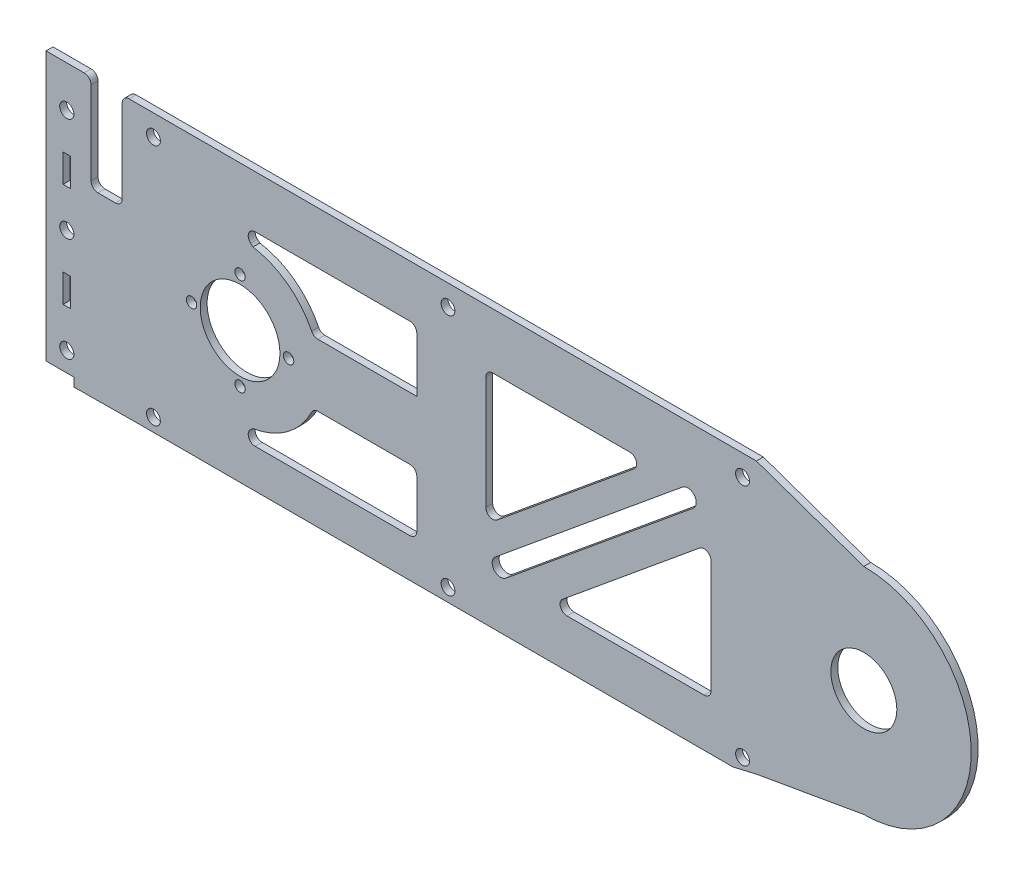
SolidWorks part; units mm, degrees
ref_plane "前视基准面" through (0, 0, 0) normal (0, 0, 1) x (1, 0, 0)
ref_plane "上视基准面" through (0, 0, 0) normal (0, 1, 0) x (1, 0, 0)
ref_plane "右视基准面" through (0, 0, 0) normal (1, 0, 0) x (0, 0, -1)
sketch "草图1" plane through (0, 0, 0) normal (0, 0, 1) x (1, 0, 0)
  line L0 (1.6429, 32.0043) -> (1.6429, 27.9043)
  line L1 (1.6429, 18.9543) -> (1.6429, 10.9543) construction
  line L2 (0.5929, 10.9043) -> (2.6929, 10.9043)
  line L3 (0.5929, 10.9043) -> (0.5929, 19.0043)
  line L4 (0.5929, 19.0043) -> (2.6929, 19.0043)
  line L5 (2.6929, 10.9043) -> (2.6929, 19.0043)
  line L6 (0.5929, 10.9043) -> (2.6929, 19.0043) construction
  line L7 (0.5929, 19.0043) -> (2.6929, 10.9043) construction
  line L12 (1.6429, -0.0457) -> (-4.3571, -0.0457) construction
  line L13 (-4.3571, -0.0457) -> (-4.3571, 41.8043)
  line L14 (-4.3571, 41.8043) -> (262.6429, 41.8043) construction
  line L15 (262.6429, 41.8043) -> (262.6429, -38.1957) construction
  line L18 (51.6429, -0.0457) -> (97.8433, -0.0457) construction
  line L19 (51.6429, -0.0457) -> (231.6429, -0.0457) construction
  line L21 (200.6429, -0.0457) -> (200.6429, 41.8043) construction
  line L23 (200.6429, 41.8043) -> (231.6429, 30.9543)
  line L26 (231.6429, -31.0457) -> (200.6561, -36.4559)
  line L28 (-4.3571, 41.8043) -> (8.6429, 41.8043)
  line L29 (1.6429, -0.0457) -> (37.6429, -0.0457) construction
  line L32 (22.4658, -38.0457) -> (193.8469, -38.0457)
  line L42 (17.6429, 13.8043) -> (17.6429, 41.8043)
  line L43 (17.6429, 41.8043) -> (200.6429, 41.8043)
  line L44 (8.6429, 41.8043) -> (8.6429, 13.8043)
  line L45 (8.6429, 13.8043) -> (17.6429, 13.8043)
  line L47 (193.8469, -38.0457) -> (200.6561, -36.4559)
  line L48 (0.5929, -19.0957) -> (2.6929, -10.9957) construction
  line L49 (0.5929, -10.9957) -> (2.6929, -19.0957) construction
  line L50 (1.6429, -19.0457) -> (1.6429, -11.0457) construction
  line L51 (2.6929, -10.9957) -> (2.6929, -19.0957)
  line L52 (0.5929, -19.0957) -> (2.6929, -19.0957)
  line L53 (0.5929, -10.9957) -> (0.5929, -19.0957)
  line L54 (0.5929, -10.9957) -> (2.6929, -10.9957)
  line L55 (-4.3571, -35.7026) -> (3.7929, -35.7026)
  line L56 (3.7929, -35.7026) -> (3.7929, -38.1957)
  line L57 (3.7929, -38.1957) -> (22.4658, -38.0457)
  line L58 (-4.3571, -35.7026) -> (-4.3571, -0.0457)
  circle A0 centre (1.6429, 29.9543) radius 2.05
  circle A1 centre (1.6429, -0.0457) radius 2.05
  circle A2 centre (1.6429, -30.0457) radius 2.05
  circle A3 centre (51.6429, -0.0457) radius 11.5
  circle A4 centre (51.6429, -0.0457) radius 14 construction
  circle A5 centre (51.6429, -14.0457) radius 1.5
  circle A12 centre (37.6429, -0.0457) radius 1.5
  circle A13 centre (51.6429, 13.9543) radius 1.5
  circle A14 centre (65.6429, -0.0457) radius 1.5
  circle A15 centre (231.6429, -0.0457) radius 9.525
  circle A16 centre (231.6429, -0.0457) radius 31 construction
  arc A17 (231.6429, 30.9543) -> (231.6429, -31.0457) centre (231.6429, -0.0457) cw
  point P6 (1.6429, 14.9543)
  point P56 (1.6429, -15.0457)
  dimension "D3" = 23
  dimension "D4" = 4
  dimension "D13" = 19.05
  dimension "D1" = 8.1
  dimension "D2" = 2.1
  dimension "D5" = 50
  dimension "D6" = 28
  dimension "D7" = 15
  dimension "D8" = 60
  dimension "D9" = 30
  dimension "D11" = 41.85
  dimension "D12" = 31
  dimension "D14" = 180
  dimension "D17" = 13
extrude "凸台-拉伸1" add sketch "草图1" along normal blind 2
sketch "草图2" plane through (0, 0, 2) normal (0, 0, 1) x (1, 0, 0)
  line L0 (111.6429, -34.2457) -> (196.6429, 35.7543) construction
  line L1 (196.6429, 35.7543) -> (196.6429, -34.2457) construction
  line L2 (196.6429, -34.2457) -> (111.6429, -34.2457) construction
  line L3 (187.5429, -24.2457) -> (140.4162, -24.2457)
  line L4 (140.4162, -24.2457) -> (187.5429, 14.5645)
  line L5 (187.5429, 14.5645) -> (187.5429, -24.2457)
  line L6 (111.6429, -34.2457) -> (111.6429, 35.7543) construction
  line L7 (111.6429, 35.7543) -> (196.6429, 35.7543) construction
  line L8 (122.5429, 25.7543) -> (169.6695, 25.7543)
  line L9 (122.5429, -13.0559) -> (169.6695, 25.7543)
  line L10 (122.5429, -13.0559) -> (122.5429, 25.7543)
  line L11 (26.6429, 35.7543) -> (51.6429, 13.9543) construction
  line L13 (65.6429, -0.0457) -> (111.6429, -0.0457) construction
  line L18 (17.6429, 41.8043) -> (200.6429, 41.8043) construction
  line L19 (17.6429, 13.8043) -> (17.6429, 41.8043) construction
  line L20 (126.8224, -21.7449) -> (180.8575, 22.7546) construction
  line L23 (26.6429, 35.7543) -> (111.6429, 35.7543) construction
  line L24 (111.6429, -0.0457) -> (111.6429, 35.7543) construction
  line L25 (72.8089, 8.9543) -> (102.6429, 8.9543)
  line L26 (102.6429, 8.9543) -> (102.6429, 26.7543)
  line L27 (50.6579, 26.7543) -> (102.6429, 26.7543)
  line L28 (50.6579, 26.7543) -> (55.3631, 22.6514)
  line L29 (102.6429, -9.0457) -> (102.6429, -26.8457)
  line L30 (72.8089, -9.0457) -> (102.6429, -9.0457)
  line L31 (50.6579, -26.8457) -> (55.3631, -22.7429)
  line L32 (50.6579, -26.8457) -> (102.6429, -26.8457)
  line L38 (125.279, -19.8708) -> (179.3141, 24.6287)
  line L39 (128.3658, -23.619) -> (182.4009, 20.8805)
  circle A0 centre (26.6429, 35.7543) radius 2
  circle A1 centre (111.6429, 35.7543) radius 2
  circle A2 centre (196.6429, 35.7543) radius 2
  circle A3 centre (111.6429, -34.2457) radius 2
  circle A4 centre (196.6429, -34.2457) radius 2
  circle A5 centre (26.6429, -34.2457) radius 2
  arc A8 (51.6429, 13.9543) -> (65.6429, -0.0457) centre (51.6429, -0.0457) cw construction
  arc A9 (55.3631, 22.6514) -> (72.8089, 8.9543) centre (51.6429, -0.0457) cw
  arc A10 (55.3631, -22.7429) -> (72.8089, -9.0457) centre (51.6429, -0.0457) ccw
  arc A11 (125.279, -19.8708) -> (128.3658, -23.619) centre (126.8224, -21.7449) ccw
  arc A12 (182.4009, 20.8805) -> (179.3141, 24.6287) centre (180.8575, 22.7546) ccw
  point P24 (26.6429, 35.8043)
  point P31 (153.84, 0.5049)
  dimension "D3" = 9
  dimension "D4" = 9
  dimension "D1" = 6
  dimension "D2" = 9
  dimension "D5" = 85
  dimension "D6" = 85
  dimension "D7" = 70
extrude "切除-拉伸1" cut sketch "草图2" against normal blind 4
fillet "圆角1" radius 2 17 edges at (187.5429, -24.2457, 1) (140.4162, -24.2457, 1) (187.5429, 14.5645, 1) (169.6695, 25.7543, 1) (122.5429, -13.0559, 1) (122.5429, 25.7543, 1) (72.8089, 8.9543, 1) (72.8089, -9.0457, 1) (50.6579, -26.8457, 1) (102.6429, -26.8457, 1) (50.6579, 26.7543, 1) (102.6429, 26.7543, 1) (102.6429, -9.0457, 1) (17.6429, 41.8043, 1) (8.6429, 41.8043, 1) (17.6429, 13.8043, 1) (8.6429, 13.8043, 1)
